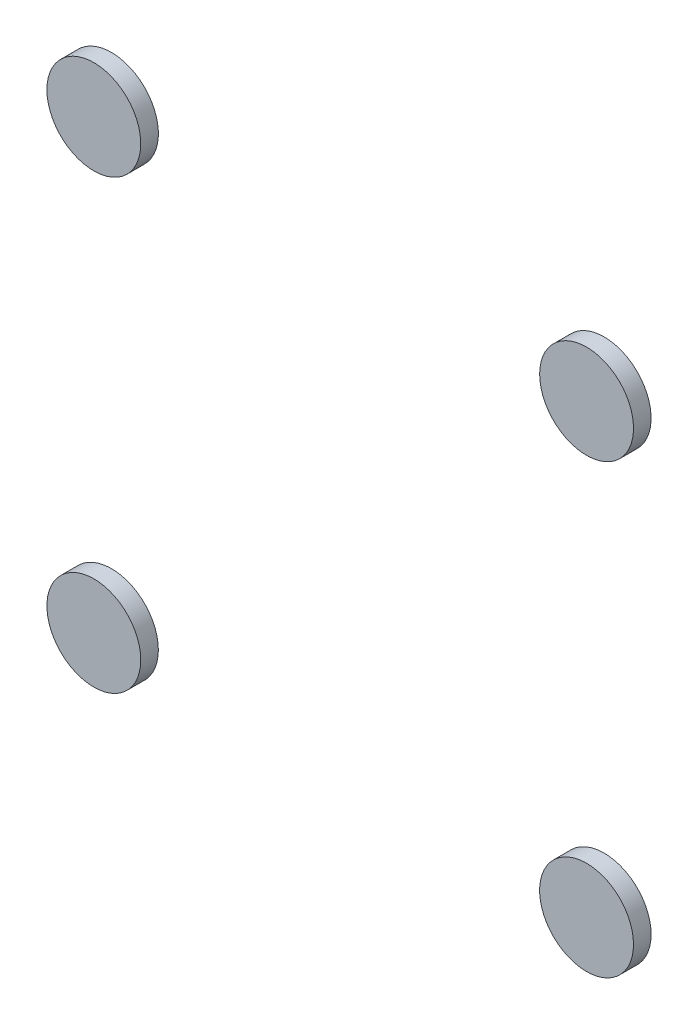
SolidWorks part; units mm, degrees
ref_plane "前视基准面" through (0, 0, 0) normal (0, 0, 1) x (1, 0, 0)
ref_plane "上视基准面" through (0, 0, 0) normal (0, 1, 0) x (1, 0, 0)
ref_plane "右视基准面" through (0, 0, 0) normal (1, 0, 0) x (0, 0, -1)
sketch "草图2" plane through (0, 0, 0) normal (0, 0, 1) x (1, 0, 0)
  line L0 (0, 0) -> (-61.0822, 0) construction
  line L1 (11, -19.0526) -> (0, 0) construction
  line L2 (-31, -19.0526) -> (-20, 0) construction
  circle A0 centre (11, -19.0526) radius 4
  circle A1 centre (-31, -19.0526) radius 4
  circle A2 centre (-31, 19.0526) radius 4
  circle A3 centre (11, 19.0526) radius 4
  point P7 (0, 0)
  dimension "D1" = 22
  dimension "D2" = 8
  dimension "D3" = 60
  dimension "D4" = 60
extrude "凸台-拉伸1" add sketch "草图2" along normal blind 1.5
